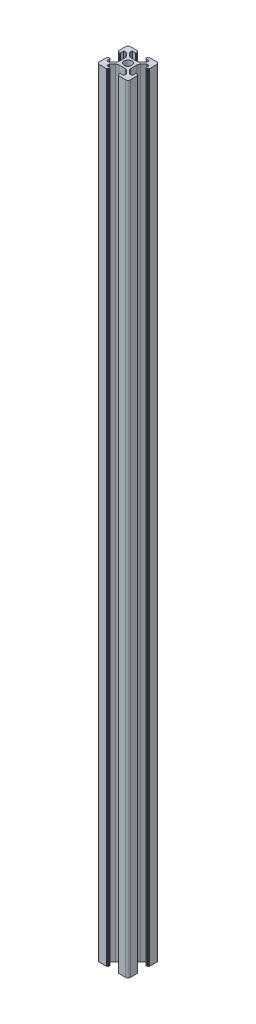
SolidWorks part; units mm, degrees
ref_plane "前视基准面" through (0, 0, 0) normal (0, 0, 1) x (1, 0, 0)
ref_plane "上视基准面" through (0, 0, 0) normal (0, 1, 0) x (1, 0, 0)
ref_plane "右视基准面" through (0, 0, 0) normal (1, 0, 0) x (0, 0, -1)
sketch "草图1" plane through (0, 0, 0) normal (0, 0, 1) x (1, 0, 0)
  line L0 (-84.2105, 190.3509) -> (-84.2105, -309.6491)
  dimension "D1" = 500
other "20 2020(1)"
ref_plane "基准面4" through (-84.2105, 190.3509, 0) normal (0, -1, 0) x (1, 0, 0)
sketch "草图11" plane through (-84.2105, 190.3509, 0) normal (0, -1, 0) x (1, 0, 0)
  line L0 (3.9, 0) -> (3.9, -2.0109)
  line L1 (4.4858, -3.4251) -> (6.5607, -5.5)
  line L2 (6.5607, -5.5) -> (7.9, -5.5)
  line L3 (8.2, -5.2) -> (8.2, -3.4)
  line L4 (8.5, -3.1) -> (9.2, -3.1)
  line L5 (9.5, -3.4) -> (9.5, -3.6)
  line L6 (9.5, -3.6) -> (9.7, -3.6)
  line L7 (10, -3.9) -> (10, -8.5)
  line L8 (8.5, -10) -> (3.9, -10)
  line L9 (3.1, -9.2) -> (3.1, -8.5)
  line L10 (3.4, -8.2) -> (5.2, -8.2)
  line L11 (5.5, -7.9) -> (5.5, -6.6849)
  line L12 (5.4121, -6.4728) -> (3.4251, -4.4858)
  line L13 (2.0109, -3.9) -> (0, -3.9)
  line L14 (0, -3.9) -> (-2.0109, -3.9)
  line L15 (-3.4251, -4.4858) -> (-5.4121, -6.4728)
  line L16 (-5.5, -6.6849) -> (-5.5, -7.9)
  line L17 (-5.2, -8.2) -> (-3.4, -8.2)
  line L18 (-3.1, -8.5) -> (-3.1, -9.2)
  line L19 (-3.9, -10) -> (-8.5, -10)
  line L20 (-10, -8.5) -> (-10, -3.9)
  line L21 (-9.7, -3.6) -> (-9.5, -3.6)
  line L22 (-9.5, -3.6) -> (-9.5, -3.4)
  line L23 (-9.2, -3.1) -> (-8.5, -3.1)
  line L24 (-8.2, -3.4) -> (-8.2, -5.2)
  line L25 (-7.9, -5.5) -> (-6.6849, -5.5)
  line L26 (-6.4728, -5.4121) -> (-4.4858, -3.4251)
  line L27 (-3.9, -2.0109) -> (-3.9, 0)
  line L28 (-3.9, 0) -> (-3.9, 2.0109)
  line L29 (-4.4858, 3.4251) -> (-6.4728, 5.4121)
  line L30 (-6.6849, 5.5) -> (-7.9, 5.5)
  line L31 (-8.2, 5.2) -> (-8.2, 3.4)
  line L32 (-8.5, 3.1) -> (-9.2, 3.1)
  line L33 (-9.5, 3.4) -> (-9.5, 3.6)
  line L34 (-9.5, 3.6) -> (-9.7, 3.6)
  line L35 (-10, 3.9) -> (-10, 8.5)
  line L36 (-8.5, 10) -> (-3.9, 10)
  line L37 (-3.6, 9.7) -> (-3.6, 9.5)
  line L38 (-3.6, 9.5) -> (-3.4, 9.5)
  line L39 (-3.1, 9.2) -> (-3.1, 8.5)
  line L40 (-3.4, 8.2) -> (-5.2, 8.2)
  line L41 (-5.5, 7.9) -> (-5.5, 6.6849)
  line L42 (-5.4121, 6.4728) -> (-3.4251, 4.4858)
  line L43 (-2.0109, 3.9) -> (0, 3.9)
  line L44 (0, 3.9) -> (2.0109, 3.9)
  line L45 (3.4251, 4.4858) -> (5.4121, 6.4728)
  line L46 (5.5, 6.6849) -> (5.5, 7.9)
  line L47 (5.2, 8.2) -> (3.4, 8.2)
  line L48 (3.1, 8.5) -> (3.1, 9.2)
  line L49 (3.4, 9.5) -> (3.6, 9.5)
  line L50 (3.6, 9.5) -> (3.6, 9.7)
  line L51 (3.9, 10) -> (8.5, 10)
  line L52 (10, 8.5) -> (10, 3.9)
  line L53 (9.7, 3.6) -> (9.5, 3.6)
  line L54 (9.5, 3.6) -> (9.5, 3.4)
  line L55 (9.2, 3.1) -> (8.5, 3.1)
  line L56 (8.2, 3.4) -> (8.2, 5.2)
  line L57 (7.9, 5.5) -> (6.6849, 5.5)
  line L58 (6.4728, 5.4121) -> (4.4858, 3.4251)
  line L59 (3.9, 2.0109) -> (3.9, 0)
  circle A0 centre (0, 0) radius 2.5
  arc A1 (3.9, -2.0109) -> (4.4858, -3.4251) centre (5.9, -2.0109) ccw
  arc A2 (7.9, -5.5) -> (8.2, -5.2) centre (7.9, -5.2) ccw
  arc A3 (8.5, -3.1) -> (8.2, -3.4) centre (8.5, -3.4) ccw
  arc A4 (9.5, -3.4) -> (9.2, -3.1) centre (9.2, -3.4) ccw
  arc A5 (10, -3.9) -> (9.7, -3.6) centre (9.7, -3.9) ccw
  arc A6 (8.5, -10) -> (10, -8.5) centre (8.5, -8.5) ccw
  arc A7 (3.6, -9.7) -> (3.9, -10) centre (3.9, -9.7) ccw
  arc A8 (3.6, -9.7) -> (3.4, -9.5) centre (3.4, -9.7) ccw
  arc A9 (3.1, -9.2) -> (3.4, -9.5) centre (3.4, -9.2) ccw
  arc A10 (3.4, -8.2) -> (3.1, -8.5) centre (3.4, -8.5) ccw
  arc A11 (5.2, -8.2) -> (5.5, -7.9) centre (5.2, -7.9) ccw
  arc A12 (5.5, -6.6849) -> (5.4121, -6.4728) centre (5.2, -6.6849) ccw
  arc A13 (3.4251, -4.4858) -> (2.0109, -3.9) centre (2.0109, -5.9) ccw
  arc A14 (-2.0109, -3.9) -> (-3.4251, -4.4858) centre (-2.0109, -5.9) ccw
  arc A15 (-5.4121, -6.4728) -> (-5.5, -6.6849) centre (-5.2, -6.6849) ccw
  arc A16 (-5.5, -7.9) -> (-5.2, -8.2) centre (-5.2, -7.9) ccw
  arc A17 (-3.1, -8.5) -> (-3.4, -8.2) centre (-3.4, -8.5) ccw
  arc A18 (-3.4, -9.5) -> (-3.1, -9.2) centre (-3.4, -9.2) ccw
  arc A19 (-3.4, -9.5) -> (-3.6, -9.7) centre (-3.4, -9.7) ccw
  arc A20 (-3.9, -10) -> (-3.6, -9.7) centre (-3.9, -9.7) ccw
  arc A21 (-10, -8.5) -> (-8.5, -10) centre (-8.5, -8.5) ccw
  arc A22 (-9.7, -3.6) -> (-10, -3.9) centre (-9.7, -3.9) ccw
  arc A23 (-9.2, -3.1) -> (-9.5, -3.4) centre (-9.2, -3.4) ccw
  arc A24 (-8.2, -3.4) -> (-8.5, -3.1) centre (-8.5, -3.4) ccw
  arc A25 (-8.2, -5.2) -> (-7.9, -5.5) centre (-7.9, -5.2) ccw
  arc A26 (-6.6849, -5.5) -> (-6.4728, -5.4121) centre (-6.6849, -5.2) ccw
  arc A27 (-4.4858, -3.4251) -> (-3.9, -2.0109) centre (-5.9, -2.0109) ccw
  arc A28 (-3.9, 2.0109) -> (-4.4858, 3.4251) centre (-5.9, 2.0109) ccw
  arc A29 (-6.4728, 5.4121) -> (-6.6849, 5.5) centre (-6.6849, 5.2) ccw
  arc A30 (-7.9, 5.5) -> (-8.2, 5.2) centre (-7.9, 5.2) ccw
  arc A31 (-8.5, 3.1) -> (-8.2, 3.4) centre (-8.5, 3.4) ccw
  arc A32 (-9.5, 3.4) -> (-9.2, 3.1) centre (-9.2, 3.4) ccw
  arc A33 (-10, 3.9) -> (-9.7, 3.6) centre (-9.7, 3.9) ccw
  arc A34 (-8.5, 10) -> (-10, 8.5) centre (-8.5, 8.5) ccw
  arc A35 (-3.6, 9.7) -> (-3.9, 10) centre (-3.9, 9.7) ccw
  arc A36 (-3.1, 9.2) -> (-3.4, 9.5) centre (-3.4, 9.2) ccw
  arc A37 (-3.4, 8.2) -> (-3.1, 8.5) centre (-3.4, 8.5) ccw
  arc A38 (-5.2, 8.2) -> (-5.5, 7.9) centre (-5.2, 7.9) ccw
  arc A39 (-5.5, 6.6849) -> (-5.4121, 6.4728) centre (-5.2, 6.6849) ccw
  arc A40 (-3.4251, 4.4858) -> (-2.0109, 3.9) centre (-2.0109, 5.9) ccw
  arc A41 (2.0109, 3.9) -> (3.4251, 4.4858) centre (2.0109, 5.9) ccw
  arc A42 (5.4121, 6.4728) -> (5.5, 6.6849) centre (5.2, 6.6849) ccw
  arc A43 (5.5, 7.9) -> (5.2, 8.2) centre (5.2, 7.9) ccw
  arc A44 (3.1, 8.5) -> (3.4, 8.2) centre (3.4, 8.5) ccw
  arc A45 (3.4, 9.5) -> (3.1, 9.2) centre (3.4, 9.2) ccw
  arc A46 (3.9, 10) -> (3.6, 9.7) centre (3.9, 9.7) ccw
  arc A47 (10, 8.5) -> (8.5, 10) centre (8.5, 8.5) ccw
  arc A48 (9.7, 3.6) -> (10, 3.9) centre (9.7, 3.9) ccw
  arc A49 (9.2, 3.1) -> (9.5, 3.4) centre (9.2, 3.4) ccw
  arc A50 (8.2, 3.4) -> (8.5, 3.1) centre (8.5, 3.4) ccw
  arc A51 (8.2, 5.2) -> (7.9, 5.5) centre (7.9, 5.2) ccw
  arc A52 (6.6849, 5.5) -> (6.4728, 5.4121) centre (6.6849, 5.2) ccw
  arc A53 (4.4858, 3.4251) -> (3.9, 2.0109) centre (5.9, 2.0109) ccw
  point P0 (0, 0)
